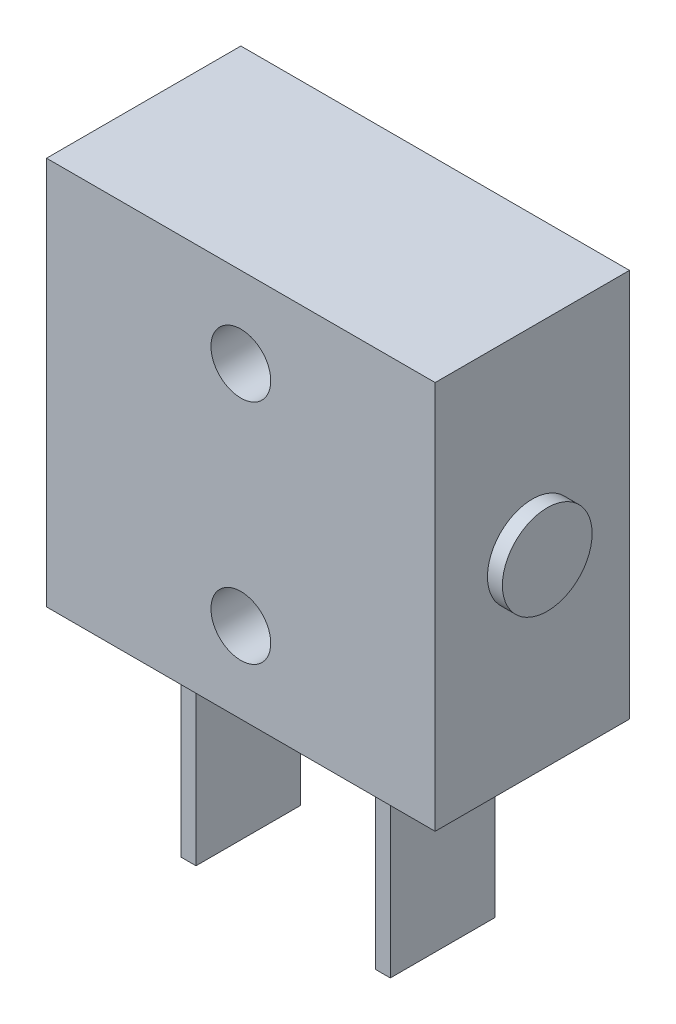
SolidWorks part; units mm, degrees
ref_plane "Front Plane" through (0, 0, 0) normal (0, 0, 1) x (1, 0, 0)
ref_plane "Top Plane" through (0, 0, 0) normal (0, 1, 0) x (1, 0, 0)
ref_plane "Right Plane" through (0, 0, 0) normal (1, 0, 0) x (0, 0, -1)
sketch "Sketch1" plane through (0, 0, 0) normal (0, 0, 1) x (1, 0, 0)
  line L1 (-6.5, 6.5) -> (6.5, 6.5)
  line L2 (-6.5, 6.5) -> (-6.5, -6.5)
  line L3 (-6.5, -6.5) -> (6.5, -6.5)
  line L4 (6.5, 6.5) -> (6.5, -6.5)
  line L5 (-6.5, 6.5) -> (6.5, -6.5) construction
  line L6 (-6.5, -6.5) -> (6.5, 6.5) construction
  point P0 (0, 0)
  dimension "D1" = 13
  dimension "D2" = 13
extrude "Boss-Extrude1" add sketch "Sketch1" along normal blind 6.5
sketch "Sketch2" plane through (0, -6.5, 0) normal (0, -1, 0) x (1, 0, 0)
  line L0 (0, 0) -> (0, 6.5) construction
  line L1 (-6.5, 6.5) -> (6.5, 6.5) construction
  line L2 (6.5, 3.25) -> (-6.5, 3.25) construction
  line L3 (6.5, 6.5) -> (6.5, 0) construction
  line L4 (-6.5, 6.5) -> (-6.5, 0) construction
  line L5 (3.5, 1.5) -> (3, 5) construction
  line L6 (-3.5, 5) -> (-3, 5)
  line L7 (-3.5, 5) -> (-3.5, 1.5)
  line L8 (-3.5, 1.5) -> (-3, 1.5)
  line L9 (-3, 5) -> (-3, 1.5)
  line L10 (-3.5, 5) -> (-3, 1.5) construction
  line L11 (-3.5, 1.5) -> (-3, 5) construction
  line L12 (3.5, 5) -> (3, 1.5) construction
  line L13 (3, 5) -> (3, 1.5)
  line L14 (3.5, 1.5) -> (3, 1.5)
  line L15 (3.5, 5) -> (3.5, 1.5)
  line L16 (3.5, 5) -> (3, 5)
  point P11 (-3.25, 3.25)
  point P20 (3.25, 3.25)
  dimension "D1" = 0.5
  dimension "D2" = 3.5
  dimension "D3" = 7
extrude "Boss-Extrude2" add sketch "Sketch2" along normal blind 6.5
sketch "Sketch3" plane through (0, 0, 6.5) normal (0, 0, 1) x (1, 0, 0)
  line L0 (0, -6.5) -> (0, 6.5) construction
  line L1 (-6.5, -6.5) -> (6.5, -6.5) construction
  line L2 (6.5, 6.5) -> (-6.5, 6.5) construction
  line L3 (-6.5, 0) -> (6.5, 0) construction
  line L4 (-6.5, 6.5) -> (-6.5, -6.5) construction
  line L5 (6.5, -6.5) -> (6.5, 6.5) construction
  circle A0 centre (0, 3.8) radius 1
  circle A1 centre (0, -3.8) radius 1
  point P16 (0, 0)
  point P17 (0, 0)
  dimension "D2" = 2
  dimension "D1" = 7.6
extrude "Cut-Extrude1" cut sketch "Sketch3" against normal through all
sketch "Sketch4" plane through (6.5, 0, 0) normal (1, 0, 0) x (0, 0, -1)
  line L0 (0, 0) -> (-6.5, 0) construction
  line L1 (-6.5, -6.5) -> (-6.5, 6.5) construction
  line L2 (-3.25, 6.5) -> (-3.25, -6.5) construction
  line L3 (-6.5, 6.5) -> (0, 6.5) construction
  line L4 (-6.5, -6.5) -> (0, -6.5) construction
  circle A0 centre (-3.25, 0) radius 1.5
  dimension "D1" = 3
extrude "Boss-Extrude3" add sketch "Sketch4" along normal blind 0.5
